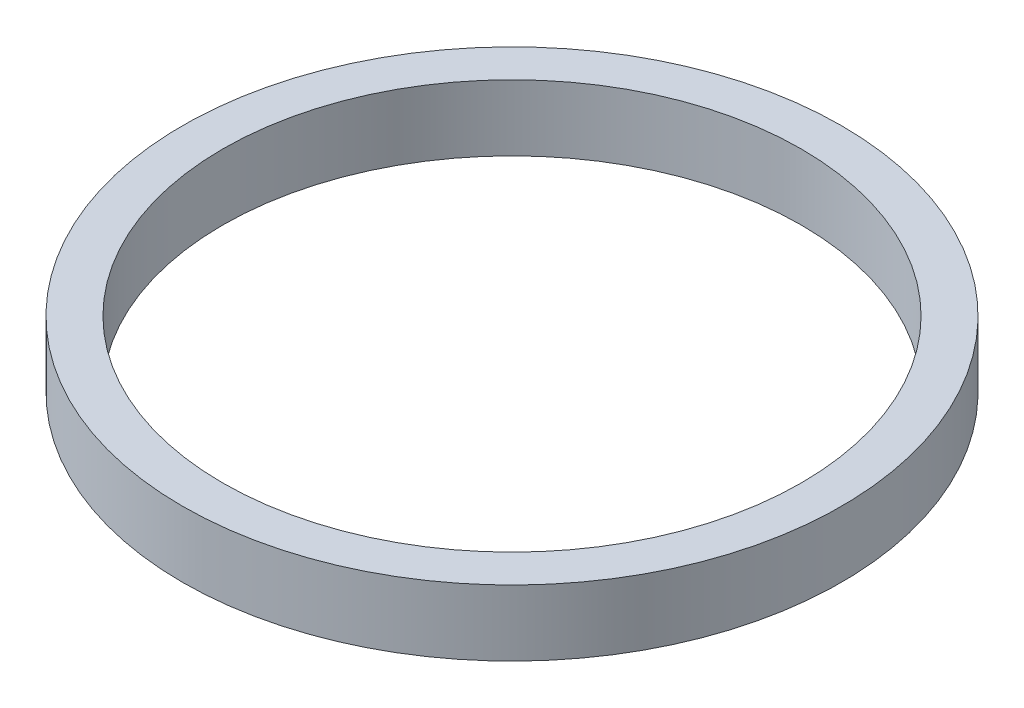
SolidWorks part; units mm, degrees
ref_plane "Front Plane" through (0, 0, 0) normal (0, 0, 1) x (1, 0, 0)
ref_plane "Top Plane" through (0, 0, 0) normal (0, 1, 0) x (1, 0, 0)
ref_plane "Right Plane" through (0, 0, 0) normal (1, 0, 0) x (0, 0, -1)
sketch "Sketch1" plane through (0, 0, 0) normal (0, 1, 0) x (1, 0, 0)
  circle A0 centre (0, 0) radius 9
  circle A1 centre (0, 0) radius 7.9
  dimension "D1" = 15.8
  dimension "D2" = 18
extrude "Boss-Extrude1" add sketch "Sketch1" along normal blind 1.8 contours A0 A1 | A1
